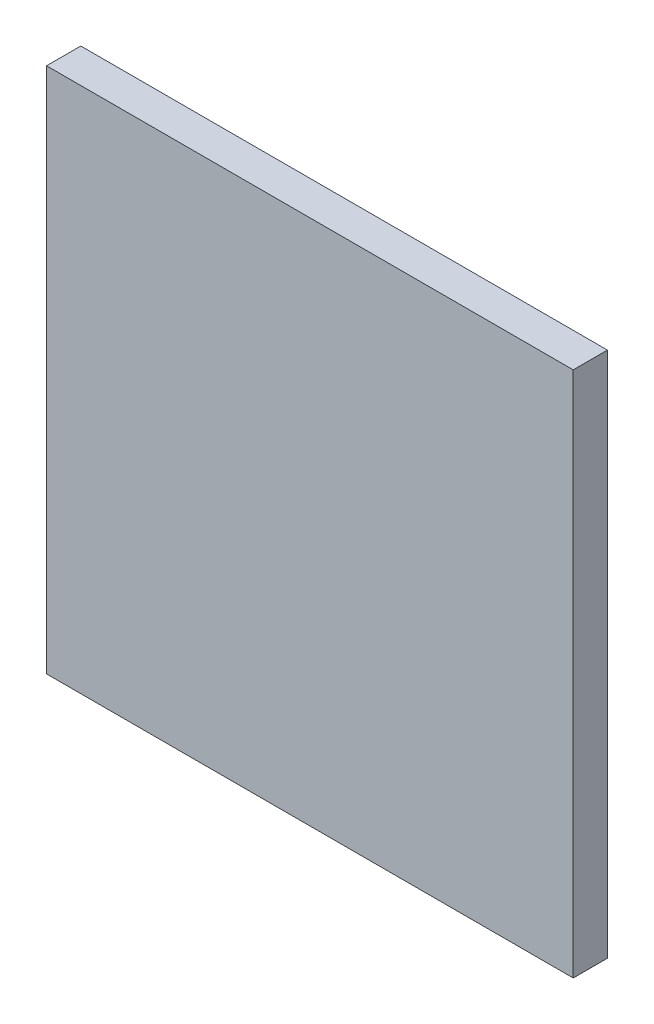
SolidWorks part; units mm, degrees
ref_plane "Front Plane" through (0, 0, 0) normal (0, 0, 1) x (1, 0, 0)
ref_plane "Top Plane" through (0, 0, 0) normal (0, 1, 0) x (1, 0, 0)
ref_plane "Right Plane" through (0, 0, 0) normal (1, 0, 0) x (0, 0, -1)
sketch "Sketch2" plane through (0, 0, 0) normal (0, 0, 1) x (1, 0, 0)
  line L1 (0, 0) -> (-10, 0)
  line L2 (0, 0) -> (0, -10)
  line L3 (0, -10) -> (-10, -10)
  line L4 (-10, 0) -> (-10, -10)
  dimension "D1" = 10
  dimension "D2" = 10
extrude "Boss-Extrude1" add sketch "Sketch2" along normal blind 0.65
